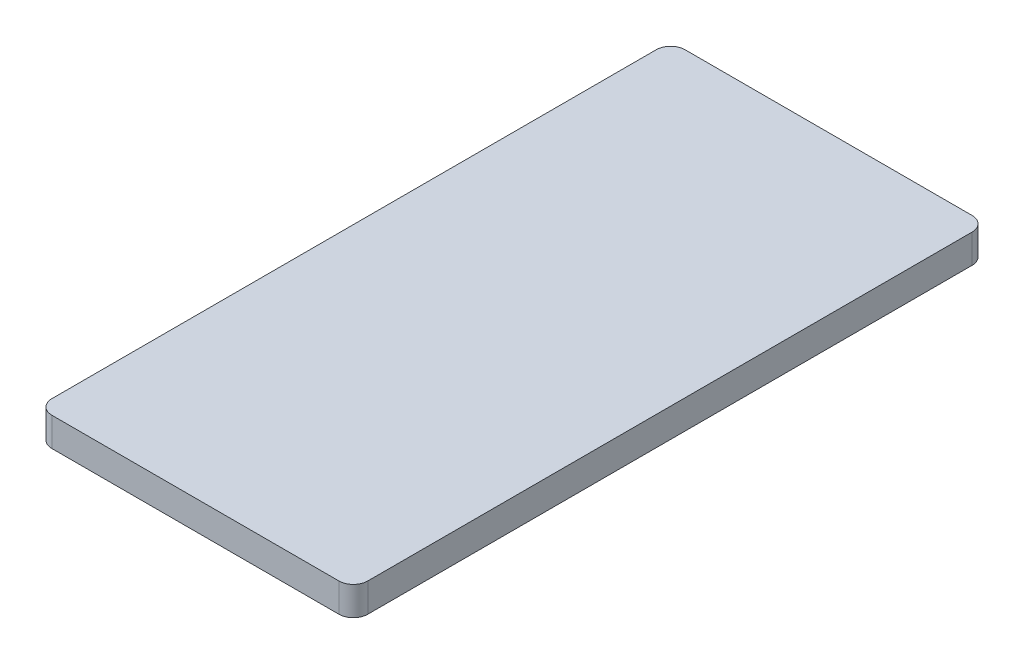
SolidWorks part; units mm, degrees
ref_plane "Front Plane" through (0, 0, 0) normal (0, 0, 1) x (1, 0, 0)
ref_plane "Top Plane" through (0, 0, 0) normal (0, 1, 0) x (1, 0, 0)
ref_plane "Right Plane" through (0, 0, 0) normal (1, 0, 0) x (0, 0, -1)
sketch "Sketch1" plane through (0, 0, 0) normal (0, 1, 0) x (1, 0, 0)
  line L1 (-12.6365, -27.8765) -> (12.6365, -27.8765)
  line L2 (-13.9065, -26.6065) -> (-13.9065, 26.6065)
  line L3 (-12.6365, 27.8765) -> (12.6365, 27.8765)
  line L4 (13.9065, -26.6065) -> (13.9065, 26.6065)
  line L5 (-13.9065, -27.8765) -> (13.9065, 27.8765) construction
  line L6 (-13.9065, 27.8765) -> (13.9065, -27.8765) construction
  arc A0 (-12.6365, -27.8765) -> (-13.9065, -26.6065) centre (-12.6365, -26.6065) cw
  arc A1 (12.6365, -27.8765) -> (13.9065, -26.6065) centre (12.6365, -26.6065) ccw
  arc A2 (12.6365, 27.8765) -> (13.9065, 26.6065) centre (12.6365, 26.6065) cw
  arc A3 (-13.9065, 26.6065) -> (-12.6365, 27.8765) centre (-12.6365, 26.6065) cw
  point P0 (0, 0)
  dimension "D3" = 1.27
  dimension "D1" = 27.813
  dimension "D2" = 55.753
extrude "Boss-Extrude1" add sketch "Sketch1" along normal blind 2.54
